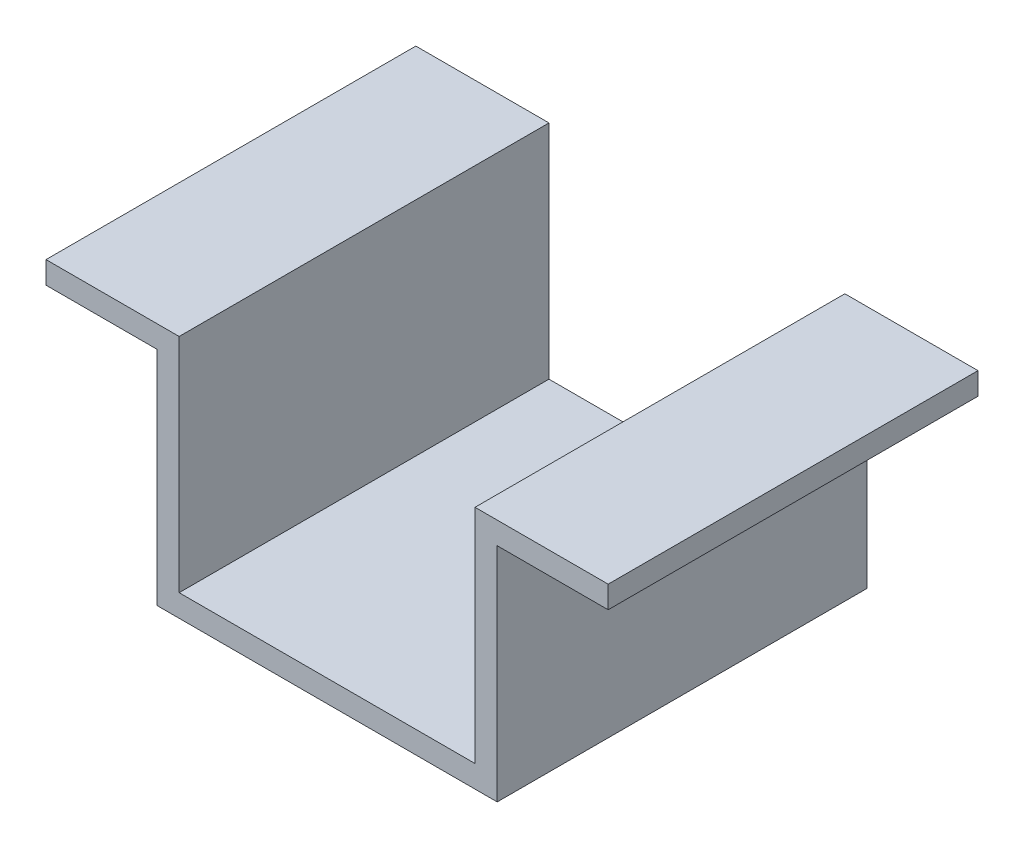
SolidWorks part; units mm, degrees
ref_plane "Front Plane" through (0, 0, 0) normal (0, 0, 1) x (1, 0, 0)
ref_plane "Top Plane" through (0, 0, 0) normal (0, 1, 0) x (1, 0, 0)
ref_plane "Right Plane" through (0, 0, 0) normal (1, 0, 0) x (0, 0, -1)
sketch "Sketch1" plane through (0, 0, 0) normal (0, 0, 1) x (1, 0, 0)
  line L0 (11.5, 38.0912) -> (11.5, 23.0912)
  line L6 (0, 20.8773) -> (0, 44.2134) construction
  line L8 (20, 39.5912) -> (-20, 39.5912) construction
  line L9 (10, 39.5912) -> (19, 39.5912)
  line L10 (19, 39.5912) -> (19, 38.0912)
  line L11 (19, 38.0912) -> (11.5, 38.0912)
  line L15 (-10, 24.5912) -> (10, 24.5912)
  line L19 (10, 39.5912) -> (10, 24.5912)
  line L28 (-10, 39.5912) -> (-10, 24.5912)
  line L29 (-11.5, 23.0912) -> (11.5, 23.0912)
  line L31 (-19, 38.0912) -> (-11.5, 38.0912)
  line L32 (-19, 39.5912) -> (-19, 38.0912)
  line L33 (-10, 39.5912) -> (-19, 39.5912)
  line L34 (-11.5, 38.0912) -> (-11.5, 23.0912)
  point P14 (0, 23.0912)
  point P15 (0, 24.5912)
  dimension "D2" = 1.5
  dimension "D4" = 15
  dimension "D5" = 7.5
  dimension "D3" = 11.5
  dimension "D9" = 1.5
  dimension "D10" = 1.5
extrude "Boss-Extrude1" add sketch "Sketch1" along normal blind 25
